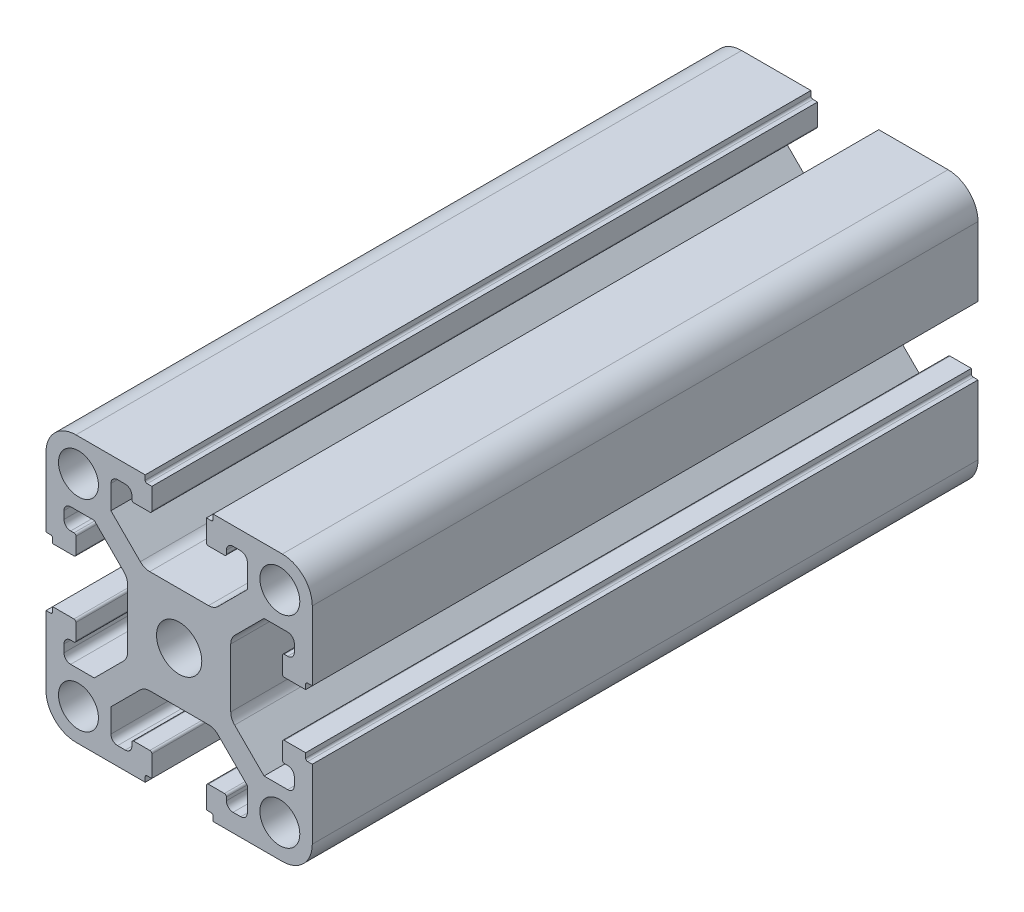
SolidWorks part; units mm, degrees
ref_plane "前视基准面" through (0, 0, 0) normal (0, 0, 1) x (1, 0, 0)
ref_plane "上视基准面" through (0, 0, 0) normal (0, 1, 0) x (1, 0, 0)
ref_plane "右视基准面" through (0, 0, 0) normal (1, 0, 0) x (0, 0, -1)
sketch "草图1" plane through (0, 0, 0) normal (0, 0, 1) x (1, 0, 0)
  line L0 (-5.28, 19.243) -> (-15.68, 19.243)
  line L1 (-20.18, 14.743) -> (-20.18, 4.343)
  line L2 (-12.9332, 9.493) -> (-16.48, 9.493)
  line L3 (-17.48, 8.493) -> (-17.48, 7.343)
  line L4 (-16.48, 6.343) -> (-15.98, 6.343)
  line L5 (-15.68, 6.043) -> (-15.68, 3.643)
  line L6 (-15.98, 3.343) -> (-19.18, 3.343)
  line L8 (-20.18, 4.343) -> (-19.48, 4.343)
  line L9 (-19.18, 4.043) -> (-19.18, 3.343)
  line L10 (-12.9332, 9.493) -> (-8.5158, 5.0756)
  line L11 (-7.93, 3.6614) -> (-7.93, -5.1754)
  line L12 (-8.5158, -6.5896) -> (-12.9332, -11.007)
  line L13 (-10.43, -13.5102) -> (-6.0126, -9.0928)
  line L14 (-4.5984, -8.507) -> (4.2384, -8.507)
  line L15 (5.6526, -9.0928) -> (10.07, -13.5102)
  line L16 (12.5732, -11.007) -> (8.1558, -6.5896)
  line L17 (7.57, -5.1754) -> (7.57, 3.6614)
  line L18 (8.1558, 5.0756) -> (12.5732, 9.493)
  line L19 (10.07, 11.9961) -> (5.6526, 7.5788)
  line L20 (4.2384, 6.993) -> (-4.5984, 6.993)
  line L21 (-6.0126, 7.5788) -> (-10.43, 11.9961)
  line L22 (-5.28, 19.243) -> (-5.28, 18.543)
  line L23 (-4.98, 18.243) -> (-4.28, 18.243)
  line L24 (-10.43, 11.9961) -> (-10.43, 15.543)
  line L25 (-9.43, 16.543) -> (-8.28, 16.543)
  line L26 (-7.28, 15.543) -> (-7.28, 15.043)
  line L27 (-6.98, 14.743) -> (-4.58, 14.743)
  line L28 (-4.28, 15.043) -> (-4.28, 18.243)
  line L29 (4.92, 19.243) -> (15.32, 19.243)
  line L30 (19.82, 14.743) -> (19.82, 4.343)
  line L31 (12.5732, 9.493) -> (16.12, 9.493)
  line L32 (17.12, 8.493) -> (17.12, 7.343)
  line L33 (16.12, 6.343) -> (15.62, 6.343)
  line L34 (15.32, 6.043) -> (15.32, 3.643)
  line L35 (15.62, 3.343) -> (18.82, 3.343)
  line L37 (19.82, 4.343) -> (19.12, 4.343)
  line L38 (18.82, 4.043) -> (18.82, 3.343)
  line L39 (10.07, 11.9961) -> (10.07, 15.543)
  line L40 (9.07, 16.543) -> (7.92, 16.543)
  line L41 (6.92, 15.543) -> (6.92, 15.043)
  line L42 (6.62, 14.743) -> (4.22, 14.743)
  line L43 (3.92, 15.043) -> (3.92, 18.243)
  line L44 (4.92, 19.243) -> (4.92, 18.543)
  line L45 (4.62, 18.243) -> (3.92, 18.243)
  line L46 (-5.28, -20.757) -> (-15.68, -20.757)
  line L47 (-20.18, -16.257) -> (-20.18, -5.857)
  line L49 (-12.9332, -11.007) -> (-16.48, -11.007)
  line L50 (-17.48, -10.007) -> (-17.48, -8.857)
  line L51 (-16.48, -7.857) -> (-15.98, -7.857)
  line L52 (-15.68, -7.557) -> (-15.68, -5.157)
  line L53 (-15.98, -4.857) -> (-19.18, -4.857)
  line L54 (-20.18, -5.857) -> (-19.48, -5.857)
  line L55 (-19.18, -5.557) -> (-19.18, -4.857)
  line L56 (-10.43, -13.5102) -> (-10.43, -17.057)
  line L57 (-9.43, -18.057) -> (-8.28, -18.057)
  line L58 (-7.28, -17.057) -> (-7.28, -16.557)
  line L59 (-6.98, -16.257) -> (-4.58, -16.257)
  line L60 (-4.28, -16.557) -> (-4.28, -19.757)
  line L61 (-5.28, -20.757) -> (-5.28, -20.057)
  line L62 (-4.98, -19.757) -> (-4.28, -19.757)
  line L63 (4.92, -20.757) -> (15.32, -20.757)
  line L64 (19.82, -16.257) -> (19.82, -5.857)
  line L66 (12.5732, -11.007) -> (16.12, -11.007)
  line L67 (17.12, -10.007) -> (17.12, -8.857)
  line L68 (16.12, -7.857) -> (15.62, -7.857)
  line L69 (15.32, -7.557) -> (15.32, -5.157)
  line L70 (15.62, -4.857) -> (18.82, -4.857)
  line L71 (19.82, -5.857) -> (19.12, -5.857)
  line L72 (18.82, -5.557) -> (18.82, -4.857)
  line L73 (10.07, -13.5102) -> (10.07, -17.057)
  line L74 (9.07, -18.057) -> (7.92, -18.057)
  line L75 (6.92, -17.057) -> (6.92, -16.557)
  line L76 (6.62, -16.257) -> (4.22, -16.257)
  line L77 (3.92, -16.557) -> (3.92, -19.757)
  line L78 (4.92, -20.757) -> (4.92, -20.057)
  line L79 (4.62, -19.757) -> (3.92, -19.757)
  arc A0 (-15.68, 19.243) -> (-20.18, 14.743) centre (-15.68, 14.743) ccw
  arc A1 (-16.48, 9.493) -> (-17.48, 8.493) centre (-16.48, 8.493) ccw
  arc A2 (-17.48, 7.343) -> (-16.48, 6.343) centre (-16.48, 7.343) ccw
  arc A3 (-15.68, 6.043) -> (-15.98, 6.343) centre (-15.98, 6.043) ccw
  arc A4 (-15.98, 3.343) -> (-15.68, 3.643) centre (-15.98, 3.643) ccw
  arc A5 (-19.18, 4.043) -> (-19.48, 4.343) centre (-19.48, 4.043) ccw
  arc A6 (-7.93, 3.6614) -> (-8.5158, 5.0756) centre (-9.93, 3.6614) ccw
  arc A7 (-8.5158, -6.5896) -> (-7.93, -5.1754) centre (-9.93, -5.1754) ccw
  arc A8 (-4.5984, -8.507) -> (-6.0126, -9.0928) centre (-4.5984, -10.507) ccw
  arc A9 (5.6526, -9.0928) -> (4.2384, -8.507) centre (4.2384, -10.507) ccw
  arc A10 (7.57, -5.1754) -> (8.1558, -6.5896) centre (9.57, -5.1754) ccw
  arc A11 (8.1558, 5.0756) -> (7.57, 3.6614) centre (9.57, 3.6614) ccw
  arc A12 (4.2384, 6.993) -> (5.6526, 7.5788) centre (4.2384, 8.993) ccw
  arc A13 (-6.0126, 7.5788) -> (-4.5984, 6.993) centre (-4.5984, 8.993) ccw
  circle A14 centre (-0.18, -0.757) radius 3.4
  circle A15 centre (-15.305, 14.368) radius 3
  arc A16 (-5.28, 18.543) -> (-4.98, 18.243) centre (-4.98, 18.543) ccw
  arc A17 (-9.43, 16.543) -> (-10.43, 15.543) centre (-9.43, 15.543) ccw
  arc A18 (-7.28, 15.543) -> (-8.28, 16.543) centre (-8.28, 15.543) ccw
  arc A19 (-7.28, 15.043) -> (-6.98, 14.743) centre (-6.98, 15.043) ccw
  arc A20 (-4.58, 14.743) -> (-4.28, 15.043) centre (-4.58, 15.043) ccw
  arc A21 (19.82, 14.743) -> (15.32, 19.243) centre (15.32, 14.743) ccw
  arc A22 (17.12, 8.493) -> (16.12, 9.493) centre (16.12, 8.493) ccw
  arc A23 (16.12, 6.343) -> (17.12, 7.343) centre (16.12, 7.343) ccw
  arc A24 (15.62, 6.343) -> (15.32, 6.043) centre (15.62, 6.043) ccw
  arc A25 (15.32, 3.643) -> (15.62, 3.343) centre (15.62, 3.643) ccw
  arc A26 (19.12, 4.343) -> (18.82, 4.043) centre (19.12, 4.043) ccw
  circle A27 centre (14.945, 14.368) radius 3
  arc A28 (10.07, 15.543) -> (9.07, 16.543) centre (9.07, 15.543) ccw
  arc A29 (7.92, 16.543) -> (6.92, 15.543) centre (7.92, 15.543) ccw
  arc A30 (6.62, 14.743) -> (6.92, 15.043) centre (6.62, 15.043) ccw
  arc A31 (3.92, 15.043) -> (4.22, 14.743) centre (4.22, 15.043) ccw
  arc A32 (4.62, 18.243) -> (4.92, 18.543) centre (4.62, 18.543) ccw
  arc A33 (-20.18, -16.257) -> (-15.68, -20.757) centre (-15.68, -16.257) ccw
  arc A34 (-17.48, -10.007) -> (-16.48, -11.007) centre (-16.48, -10.007) ccw
  arc A35 (-16.48, -7.857) -> (-17.48, -8.857) centre (-16.48, -8.857) ccw
  arc A36 (-15.98, -7.857) -> (-15.68, -7.557) centre (-15.98, -7.557) ccw
  arc A37 (-15.68, -5.157) -> (-15.98, -4.857) centre (-15.98, -5.157) ccw
  arc A38 (-19.48, -5.857) -> (-19.18, -5.557) centre (-19.48, -5.557) ccw
  circle A39 centre (-15.305, -15.882) radius 3
  arc A40 (-10.43, -17.057) -> (-9.43, -18.057) centre (-9.43, -17.057) ccw
  arc A41 (-8.28, -18.057) -> (-7.28, -17.057) centre (-8.28, -17.057) ccw
  arc A42 (-6.98, -16.257) -> (-7.28, -16.557) centre (-6.98, -16.557) ccw
  arc A43 (-4.28, -16.557) -> (-4.58, -16.257) centre (-4.58, -16.557) ccw
  arc A44 (-4.98, -19.757) -> (-5.28, -20.057) centre (-4.98, -20.057) ccw
  arc A45 (15.32, -20.757) -> (19.82, -16.257) centre (15.32, -16.257) ccw
  arc A46 (16.12, -11.007) -> (17.12, -10.007) centre (16.12, -10.007) ccw
  arc A47 (17.12, -8.857) -> (16.12, -7.857) centre (16.12, -8.857) ccw
  arc A48 (15.32, -7.557) -> (15.62, -7.857) centre (15.62, -7.557) ccw
  arc A49 (15.62, -4.857) -> (15.32, -5.157) centre (15.62, -5.157) ccw
  arc A50 (18.82, -5.557) -> (19.12, -5.857) centre (19.12, -5.557) ccw
  circle A51 centre (14.945, -15.882) radius 3
  arc A52 (9.07, -18.057) -> (10.07, -17.057) centre (9.07, -17.057) ccw
  arc A53 (6.92, -17.057) -> (7.92, -18.057) centre (7.92, -17.057) ccw
  arc A54 (6.92, -16.557) -> (6.62, -16.257) centre (6.62, -16.557) ccw
  arc A55 (4.22, -16.257) -> (3.92, -16.557) centre (4.22, -16.557) ccw
  arc A56 (4.92, -20.057) -> (4.62, -19.757) centre (4.62, -20.057) ccw
extrude "凸台-拉伸1" add sketch "草图1" along normal blind 100
